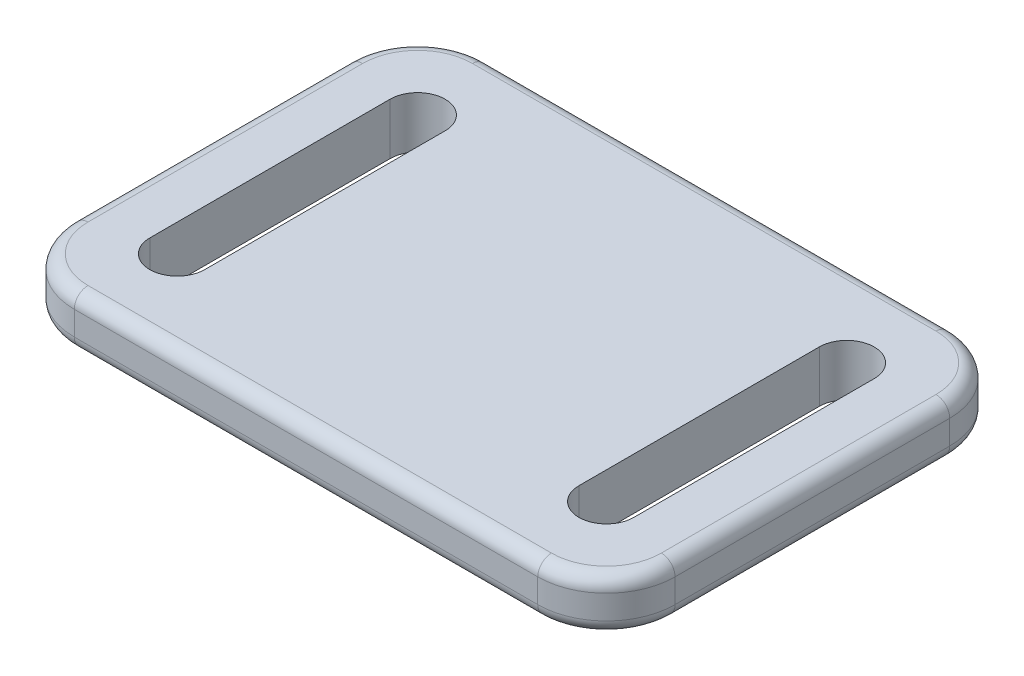
SolidWorks part; units mm, degrees
ref_plane "Front Plane" through (0, 0, 0) normal (0, 0, 1) x (1, 0, 0)
ref_plane "Top Plane" through (0, 0, 0) normal (0, 1, 0) x (1, 0, 0)
ref_plane "Right Plane" through (0, 0, 0) normal (1, 0, 0) x (0, 0, -1)
sketch "Sketch1" plane through (0, 0, 0) normal (0, 1, 0) x (1, 0, 0)
  line L1 (0, 0) -> (35, 0)
  line L2 (0, 0) -> (0, 24)
  line L3 (0, 24) -> (35, 24)
  line L4 (35, 0) -> (35, 24)
  line L5 (0, 24) -> (35, 24)
  dimension "D1" = 35
  dimension "D2" = 24
extrude "Boss-Extrude1" add sketch "Sketch1" along normal blind 3 contours L1 L4 L3 L2
sketch "Sketch2" plane through (0, 3, 0) normal (0, 1, 0) x (1, 0, 0)
  line L0 (0, 12) -> (35, 12) construction
  line L1 (0, 0) -> (0, 24) construction
  line L2 (35, 0) -> (35, 24) construction
  line L3 (5, 19) -> (5, 5) construction
  line L4 (6.6, 19) -> (6.6, 5)
  line L5 (3.4, 19) -> (3.4, 5)
  line L6 (0, 24) -> (35, 24) construction
  line L7 (17.5, 12) -> (17.5, 24) construction
  line L8 (30, 19) -> (30, 5) construction
  line L9 (28.4, 19) -> (28.4, 5)
  line L10 (31.6, 19) -> (31.6, 5)
  arc A0 (6.6, 19) -> (3.4, 19) centre (5, 19) ccw
  arc A1 (3.4, 5) -> (6.6, 5) centre (5, 5) ccw
  arc A2 (28.4, 19) -> (31.6, 19) centre (30, 19) cw
  arc A3 (31.6, 5) -> (28.4, 5) centre (30, 5) cw
  point P8 (5, 12)
  point P19 (30, 12)
  dimension "D3" = 1.6
  dimension "D1" = 5
  dimension "D2" = 5
extrude "Cut-Extrude1" cut sketch "Sketch2" against normal blind 7
fillet "Fillet1" radius 4 4 edges at (0, 1.5, -24) (0, 1.5, 0) (35, 1.5, 0) (35, 1.5, -24)
fillet "Fillet2" radius 0.8 16 edges at (33.8284, 3, -1.1716) (17.5, 3, 0) (1.1716, 3, -1.1716) (0, 3, -12) (1.1716, 3, -22.8284) (17.5, 3, -24) (33.8284, 3, -22.8284) (1.1716, 0, -1.1716) (0, 0, -12) (1.1716, 0, -22.8284) (17.5, 0, -24) (33.8284, 0, -22.8284) (35, 0, -12) (33.8284, 0, -1.1716) (35, 3, -12) (17.5, 0, 0)
